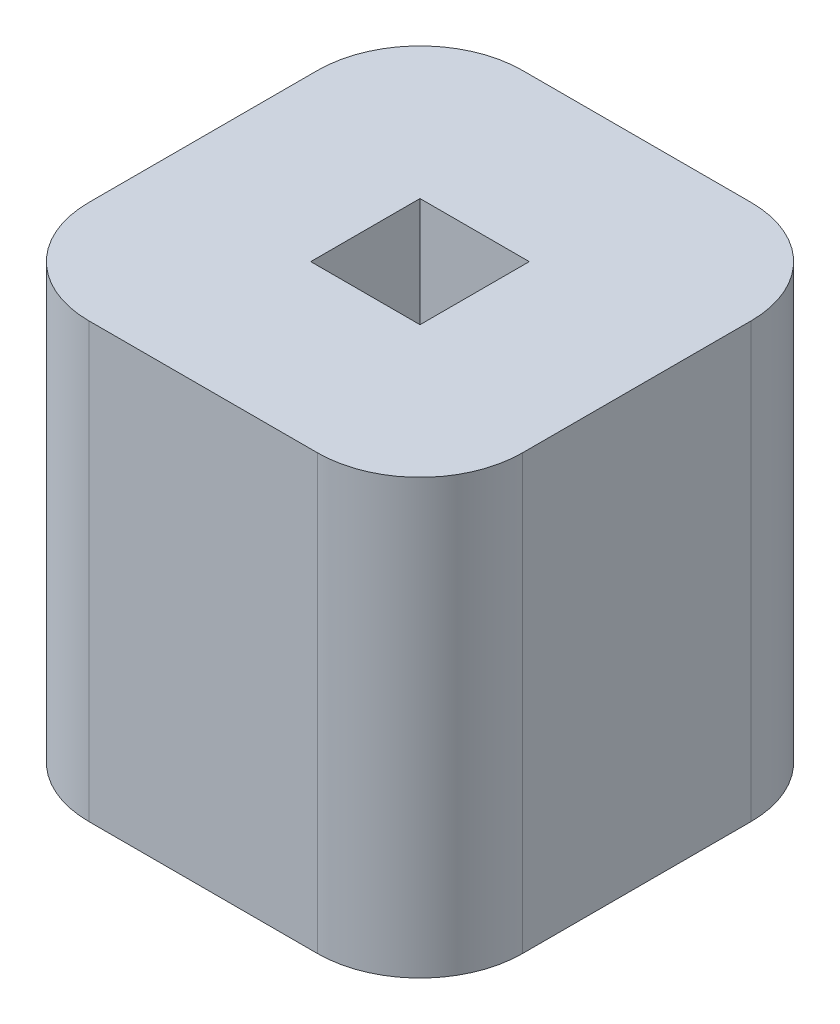
SolidWorks part; units mm, degrees
material "CA"
ref_plane "Front Plane" through (0, 0, 0) normal (0, 0, 1) x (1, 0, 0)
ref_plane "Top Plane" through (0, 0, 0) normal (0, 1, 0) x (1, 0, 0)
ref_plane "Right Plane" through (0, 0, 0) normal (1, 0, 0) x (0, 0, -1)
sketch "Sketch1" plane through (0, 0, 0) normal (0, 1, 0) x (1, 0, 0)
  line L1 (-1.0538, 1.5113) -> (1.4862, 1.5113)
  line L2 (-1.0538, 1.5113) -> (-1.0538, -1.0287)
  line L3 (-1.0538, -1.0287) -> (1.4862, -1.0287)
  line L4 (1.4862, 1.5113) -> (1.4862, -1.0287)
extrude "Boss-Extrude1" add sketch "Sketch1" along normal blind 2.54
sketch "Sketch2" plane through (0, 2.54, 0) normal (0, 1, 0) x (1, 0, 0)
  line L2 (-0.1038, -0.0787) -> (0.5362, -0.0787)
  line L3 (-0.1038, -0.0787) -> (-0.1038, 0.5613)
  line L4 (-0.1038, 0.5613) -> (0.5362, 0.5613)
  line L5 (0.5362, -0.0787) -> (0.5362, 0.5613)
  line L6 (-0.1038, -0.0787) -> (0.5362, 0.5613) construction
  line L7 (-0.1038, 0.5613) -> (0.5362, -0.0787) construction
  point P4 (0.2162, 0.2413)
extrude "Cut-Extrude1" cut sketch "Sketch2" against normal blind 2.54
fillet "Fillet2" radius 0.6 1 edges at (-1.0538, 1.27, -1.5113)
fillet "Fillet3" radius 0.6 1 edges at (-1.0538, 1.27, 1.0287)
fillet "Fillet4" radius 0.6 1 edges at (1.4862, 1.27, 1.0287)
fillet "Fillet5" radius 0.6 1 edges at (1.4862, 1.27, -1.5113)
